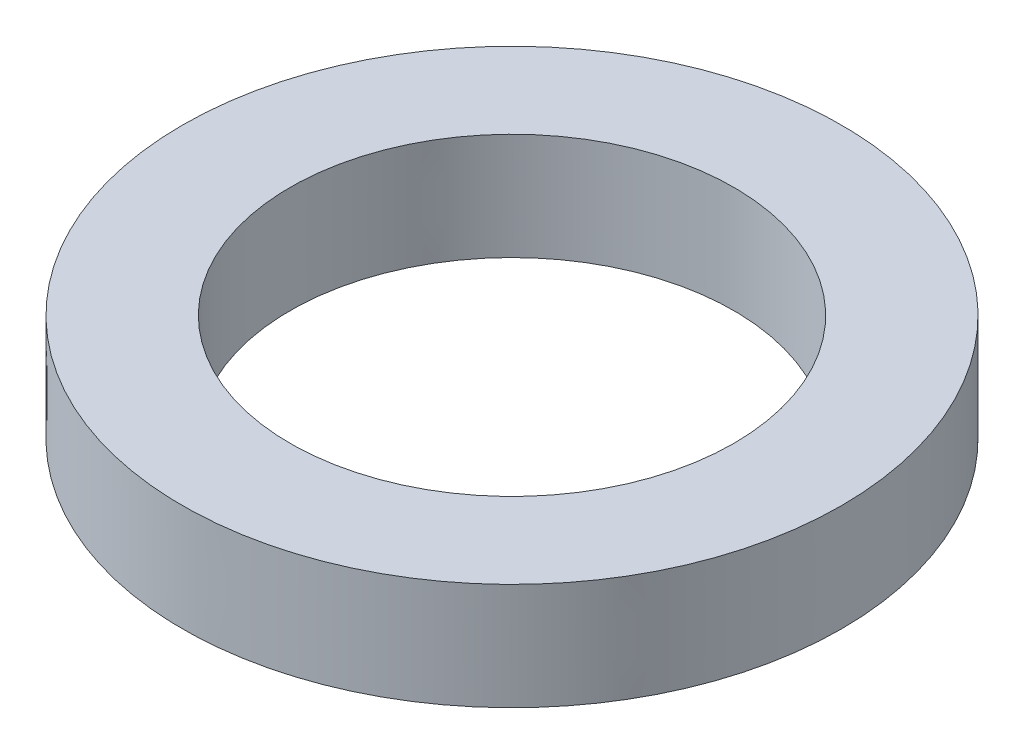
SolidWorks part; units mm, degrees
material "1.4000 (X6Cr13)"
ref_plane "Ön Düzlem" through (0, 0, 0) normal (0, 0, 1) x (1, 0, 0)
ref_plane "Üst Düzlem" through (0, 0, 0) normal (0, 1, 0) x (1, 0, 0)
ref_plane "Sağ Düzlem" through (0, 0, 0) normal (1, 0, 0) x (0, 0, -1)
sketch "Çizim1" plane through (0, 0, 0) normal (0, 0, 1) x (1, 0, 0)
  line L0 (0, 0) -> (0.0002, 4.7175) construction
  line L1 (14.5563, -0.0005) -> (14.5563, 4.717)
  line L2 (14.5563, 4.717) -> (9.7975, 4.717)
  line L3 (9.7975, 4.717) -> (9.7975, -0.0005)
  line L4 (9.7975, -0.0005) -> (11.3328, -0.0005)
  line L5 (11.3328, -0.0005) -> (12.0152, 2.7819)
  line L6 (12.0152, 2.7819) -> (12.531, 2.8101)
  line L7 (12.531, 2.8101) -> (13.6913, -0.0005)
  line L8 (13.6913, -0.0005) -> (14.5563, -0.0005)
revolve "Döndür1" add sketch "Çizim1" angle 360 about L0
